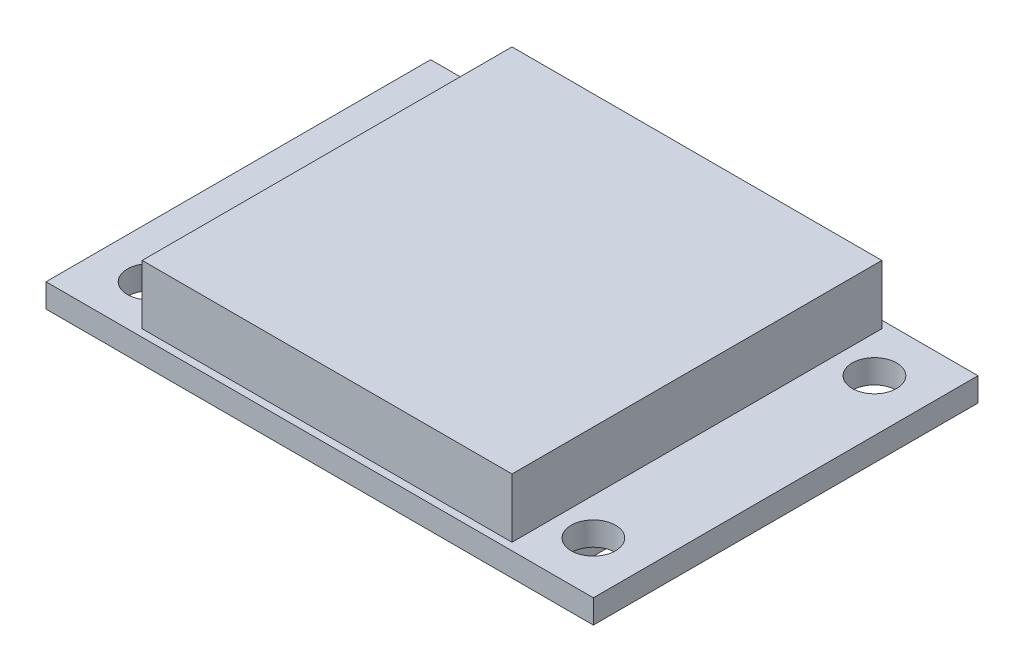
SolidWorks part; units mm, degrees
ref_plane "Front Plane" through (0, 0, 0) normal (0, 0, 1) x (1, 0, 0)
ref_plane "Top Plane" through (0, 0, 0) normal (0, 1, 0) x (1, 0, 0)
ref_plane "Right Plane" through (0, 0, 0) normal (1, 0, 0) x (0, 0, -1)
sketch "Sketch1" plane through (0, 0, 0) normal (0, 1, 0) x (1, 0, 0)
  line L0 (18.5, 26) -> (18.5, 0) construction
  line L1 (0, 0) -> (37, 0)
  line L2 (0, 0) -> (0, 26)
  line L3 (0, 26) -> (37, 26)
  line L4 (37, 0) -> (37, 26)
  line L5 (0, 13) -> (37, 13) construction
  circle A0 centre (3.5, 22.5) radius 1.5
  circle A1 centre (33.5, 22.5) radius 1.5
  circle A2 centre (33.5, 3.5) radius 1.5
  circle A3 centre (3.5, 3.5) radius 1.5
  dimension "D3" = 3
  dimension "D1" = 37
  dimension "D2" = 26
  dimension "D4" = 3.5
  dimension "D5" = 3.5
extrude "Boss-Extrude1" add sketch "Sketch1" along normal blind 1.6
sketch "Sketch2" plane through (0, 1.6, 0) normal (0, 1, 0) x (1, 0, 0)
  line L0 (18.5, 26) -> (18.5, 0) construction
  line L1 (6, 0.5) -> (31, 0.5)
  line L2 (6, 0.5) -> (6, 25.5)
  line L3 (6, 25.5) -> (31, 25.5)
  line L4 (31, 0.5) -> (31, 25.5)
  line L5 (6, 0.5) -> (31, 25.5) construction
  line L6 (6, 25.5) -> (31, 0.5) construction
  line L7 (37, 26) -> (0, 26) construction
  line L8 (0, 0) -> (37, 0) construction
  line L9 (0, 13) -> (37, 13) construction
  line L10 (0, 26) -> (0, 0) construction
  line L11 (37, 0) -> (37, 26) construction
  point P0 (18.5, 13)
  dimension "D1" = 25
extrude "Boss-Extrude2" add sketch "Sketch2" along normal blind 4
sketch "Sketch3" plane through (0, 0, 0) normal (0, -1, 0) x (1, 0, 0)
  line L0 (37, -13) -> (0, -13) construction
  line L1 (30.5658, -21) -> (18.5658, -21)
  line L2 (30.5658, -21) -> (30.5658, -5)
  line L3 (30.5658, -5) -> (18.5658, -5)
  line L4 (18.5658, -21) -> (18.5658, -5)
  line L5 (30.5658, -21) -> (18.5658, -5) construction
  line L6 (30.5658, -5) -> (18.5658, -21) construction
  line L7 (37, 0) -> (37, -26) construction
  line L8 (0, -26) -> (0, 0) construction
  point P0 (24.5658, -13)
  dimension "D1" = 12
  dimension "D2" = 16
extrude "Boss-Extrude3" add sketch "Sketch3" along normal blind 2.4
